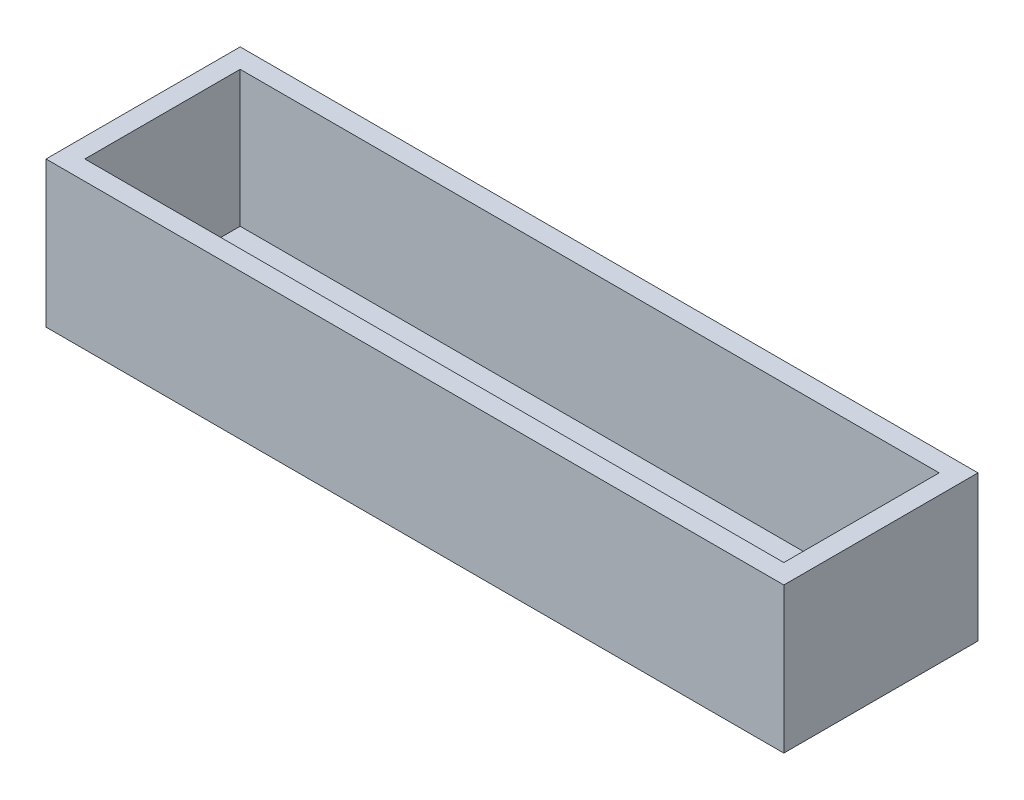
SolidWorks part; units mm, degrees
ref_plane "Front Plane" through (0, 0, 0) normal (0, 0, 1) x (1, 0, 0)
ref_plane "Top Plane" through (0, 0, 0) normal (0, 1, 0) x (1, 0, 0)
ref_plane "Right Plane" through (0, 0, 0) normal (1, 0, 0) x (0, 0, -1)
sketch "Sketch1" plane through (0, 0, 0) normal (0, 1, 0) x (1, 0, 0)
  line L1 (-38, 10) -> (38, 10)
  line L2 (-38, 10) -> (-38, -10)
  line L3 (-38, -10) -> (38, -10)
  line L4 (38, 10) -> (38, -10)
  line L5 (-38, 10) -> (38, -10) construction
  line L6 (-38, -10) -> (38, 10) construction
  point P0 (0, 0)
  dimension "D1" = 76
  dimension "D2" = 20
extrude "Boss-Extrude1" add sketch "Sketch1" along normal blind 15
sketch "Sketch2" plane through (0, 15, 0) normal (0, 1, 0) x (1, 0, 0)
  line L0 (-38, 10) -> (-38, -10) construction
  line L1 (-36, 8) -> (36, 8)
  line L2 (-36, 8) -> (-36, -8)
  line L3 (-36, -8) -> (36, -8)
  line L4 (36, 8) -> (36, -8)
  line L5 (-36, 8) -> (36, -8) construction
  line L6 (-36, -8) -> (36, 8) construction
  line L7 (-38, -10) -> (38, -10) construction
  point P0 (0, 0)
  dimension "D1" = 2
  dimension "D2" = 2
extrude "Cut-Extrude1" cut sketch "Sketch2" against normal blind 14
